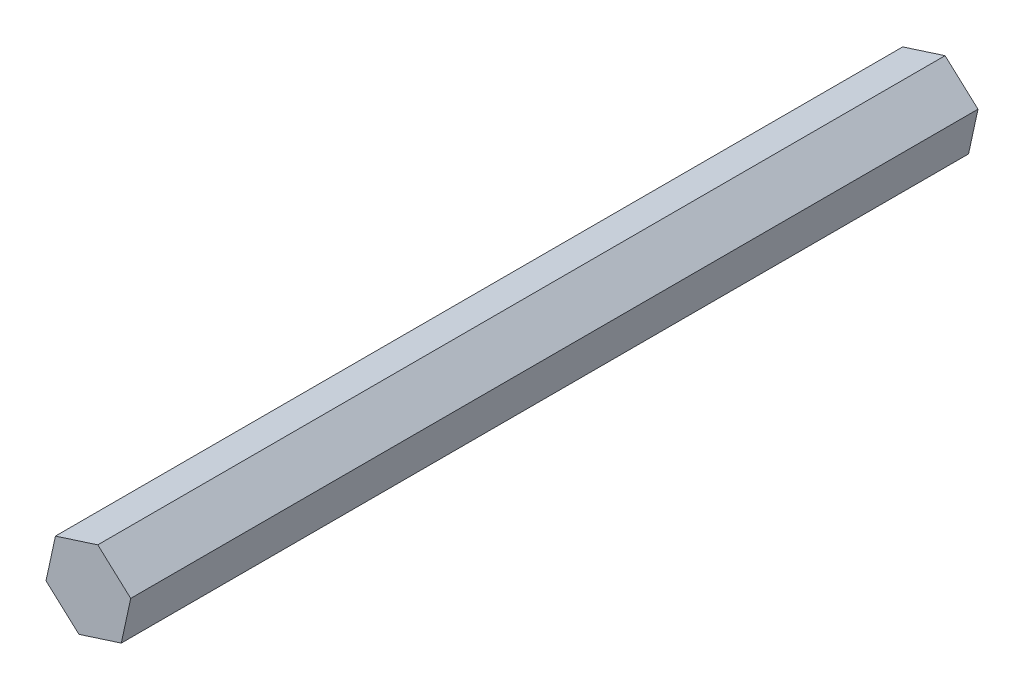
SolidWorks part; units mm, degrees
ref_plane "Front Plane" through (0, 0, 0) normal (0, 0, 1) x (1, 0, 0)
ref_plane "Top Plane" through (0, 0, 0) normal (0, 1, 0) x (1, 0, 0)
ref_plane "Right Plane" through (0, 0, 0) normal (1, 0, 0) x (0, 0, -1)
sketch "Sketch1" plane through (0, 0, 0) normal (0, 0, 1) x (1, 0, 0)
  line L1 (2.1373, -1.9404) -> (2.7491, 0.8807)
  line L2 (2.7491, 0.8807) -> (0.6118, 2.8212)
  line L3 (0.6118, 2.8212) -> (-2.1373, 1.9404)
  line L4 (-2.1373, 1.9404) -> (-2.7491, -0.8807)
  line L5 (-2.7491, -0.8807) -> (-0.6118, -2.8212)
  line L6 (-0.6118, -2.8212) -> (2.1373, -1.9404)
  circle A0 centre (0, 0) radius 2.5 construction
extrude "Boss-Extrude1" add sketch "Sketch1" along normal blind 55
